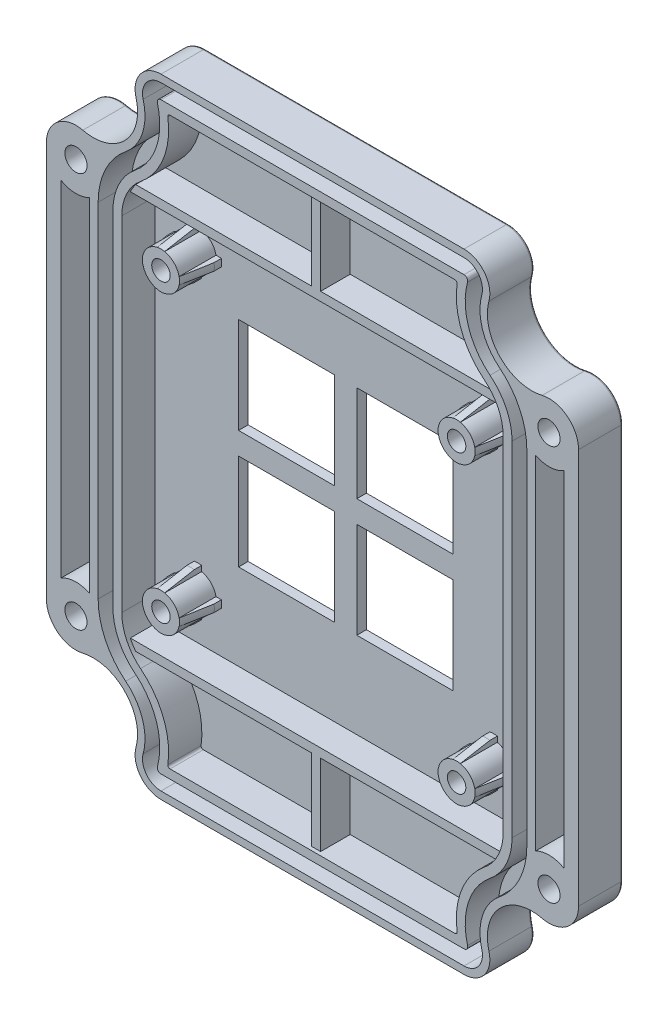
SolidWorks part; units mm, degrees
ref_plane "Front Plane" through (0, 0, 0) normal (0, 0, 1) x (1, 0, 0)
ref_plane "Top Plane" through (0, 0, 0) normal (0, 1, 0) x (1, 0, 0)
ref_plane "Right Plane" through (0, 0, 0) normal (1, 0, 0) x (0, 0, -1)
sketch "Sketch1" plane through (0, 0, 0) normal (0, 0, 1) x (1, 0, 0)
  line L12 (36, 85) -> (36, 0) construction
  line L13 (0, 42.5) -> (72, 42.5) construction
  line L14 (0, 69.25) -> (0, 15.75)
  line L15 (15.5, 0) -> (56.5, 0)
  line L16 (72, 15.75) -> (72, 69.25)
  line L17 (56.5, 85) -> (15.5, 85)
  arc A13 (12.1242, 80.5757) -> (4.9292, 73.1406) centre (6.3257, 78.9881) cw
  arc A14 (15.5, 85) -> (12.1242, 80.5757) centre (15.5, 81.5) ccw
  arc A15 (4.9292, 73.1406) -> (0, 69.25) centre (4, 69.25) ccw
  arc A16 (67.0708, 73.1406) -> (72, 69.25) centre (68, 69.25) cw
  arc A17 (56.5, 85) -> (59.8758, 80.5757) centre (56.5, 81.5) cw
  arc A18 (59.8758, 80.5757) -> (67.0708, 73.1406) centre (65.6743, 78.9881) ccw
  arc A19 (59.8758, 4.4243) -> (67.0708, 11.8594) centre (65.6743, 6.0119) cw
  arc A20 (56.5, 0) -> (59.8758, 4.4243) centre (56.5, 3.5) ccw
  arc A21 (67.0708, 11.8594) -> (72, 15.75) centre (68, 15.75) ccw
  arc A22 (4.9292, 11.8594) -> (0, 15.75) centre (4, 15.75) cw
  arc A23 (15.5, 0) -> (12.1242, 4.4243) centre (15.5, 3.5) cw
  arc A24 (12.1242, 4.4243) -> (4.9292, 11.8594) centre (6.3257, 6.0119) ccw
extrude "Boss-Extrude1" add sketch "Sketch1" along normal blind 6
sketch "Sketch2" plane through (0, 0, 6) normal (0, 0, 1) x (1, 0, 0)
  line L0 (36, 85) -> (36, 0) construction
  line L1 (0, 42.5) -> (72, 42.5) construction
  circle A0 centre (4, 69.25) radius 1.5
  circle A1 centre (68, 69.25) radius 1.5
  circle A2 centre (4, 15.75) radius 1.5
  circle A3 centre (68, 15.75) radius 1.5
  dimension "D1" = 3
extrude "Cut-Extrude1" cut sketch "Sketch2" against normal blind 6
sketch "Sketch3" plane through (0, 0, 0) normal (0, 0, -1) x (-1, 0, 0)
  circle A0 centre (-68, 69.25) radius 3
  circle A1 centre (-4, 69.25) radius 3
  circle A2 centre (-68, 15.75) radius 3
  circle A3 centre (-4, 15.75) radius 3
  dimension "D1" = 6
  dimension "D2" = 6
  dimension "D3" = 6
  dimension "D4" = 6
extrude "Cut-Extrude2" cut sketch "Sketch3" against normal blind 3
fillet "Fillet1" radius 0.3 20 edges at (0, 42.5, 0) (1.5218, 12.6102, 0) (10.646, 10.1927, 0) (12.7175, 1.3769, 0) (36, 0, 0) (59.2825, 1.3769, 0) (61.354, 10.1927, 0) (70.4782, 12.6102, 0) (72, 42.5, 0) (70.4782, 72.3898, 0) (61.354, 74.8073, 0) (59.2825, 83.6231, 0) (36, 85, 0) (12.7175, 83.6231, 0) (10.646, 74.8073, 0) (1.5218, 72.3898, 0) (65, 69.25, 0) (1, 15.75, 0) (65, 15.75, 0) (1, 69.25, 0)
sketch "Sketch4" plane through (0, 0, 0) normal (0, 0, -1) x (-1, 0, 0)
  line L1 (-58, 66.5) -> (-14, 66.5)
  line L2 (-60, 64.5) -> (-60, 20.5)
  line L3 (-58, 18.5) -> (-14, 18.5)
  line L4 (-12, 64.5) -> (-12, 20.5)
  line L5 (-36, 85) -> (-36, 0) construction
  line L6 (0, 42.5) -> (-72, 42.5) construction
  arc A0 (-60, 64.5) -> (-58, 66.5) centre (-58, 64.5) cw
  arc A1 (-12, 64.5) -> (-14, 66.5) centre (-14, 64.5) ccw
  arc A2 (-14, 18.5) -> (-12, 20.5) centre (-14, 20.5) ccw
  arc A3 (-58, 18.5) -> (-60, 20.5) centre (-58, 20.5) cw
  point P10 (-60, 66.5)
  point P15 (-12, 18.5)
  point P18 (-60, 18.5)
  dimension "D5" = 2
  dimension "D6" = 2
  dimension "D7" = 2
  dimension "D8" = 2
  dimension "D1" = 48
  dimension "D2" = 48
  dimension "D3" = 24
  dimension "D4" = 24
extrude "Cut-Extrude3" cut sketch "Sketch4" against normal blind 0.2
sketch "Sketch5" plane through (0, 0, 0.2) normal (0, 0, -1) x (-1, 0, 0)
  line L0 (-36, 85) -> (-36, 0) construction
  line L1 (-34.5, 57) -> (-21.5, 57)
  line L2 (-34.5, 57) -> (-34.5, 44)
  line L3 (-34.5, 44) -> (-21.5, 44)
  line L4 (-21.5, 57) -> (-21.5, 44)
  line L5 (0, 42.5) -> (-72, 42.5) construction
  line L6 (-36, 66.5) -> (-36, 18.5) construction
  line L7 (-14, 66.5) -> (-58, 66.5) construction
  line L8 (-58, 18.5) -> (-14, 18.5) construction
  line L9 (-60, 42.5) -> (-12, 42.5) construction
  line L10 (-60, 64.5) -> (-60, 20.5) construction
  line L11 (-12, 20.5) -> (-12, 64.5) construction
  line L12 (-50.5, 57) -> (-50.5, 44)
  line L13 (-37.5, 44) -> (-50.5, 44)
  line L14 (-37.5, 57) -> (-37.5, 44)
  line L15 (-37.5, 57) -> (-50.5, 57)
  line L16 (-37.5, 28) -> (-50.5, 28)
  line L17 (-37.5, 28) -> (-37.5, 41)
  line L18 (-37.5, 41) -> (-50.5, 41)
  line L19 (-50.5, 28) -> (-50.5, 41)
  line L20 (-21.5, 28) -> (-21.5, 41)
  line L21 (-34.5, 41) -> (-21.5, 41)
  line L22 (-34.5, 28) -> (-34.5, 41)
  line L23 (-34.5, 28) -> (-21.5, 28)
  point P6 (-28, 44)
  dimension "D1" = 13
  dimension "D2" = 13
  dimension "D3" = 1.5
  dimension "D4" = 1.5
extrude "Cut-Extrude4" cut sketch "Sketch5" against normal blind 5.8
sketch "Sketch6" plane through (0, 0, 6) normal (0, 0, 1) x (1, 0, 0)
  line L0 (7, 81.7875) -> (7, 6.0389) construction
  line L1 (0, 69.25) -> (0, 15.75) construction
  line L2 (65, 81.7875) -> (65, 3.4386) construction
  line L3 (72, 15.75) -> (72, 69.25) construction
  line L4 (2, 79.754) -> (2, -5.5734) construction
  line L5 (5.8, 81.7875) -> (5.8, -9.4813) construction
  line L6 (36, 85) -> (36, 0) construction
  line L7 (0, 42.5) -> (72, 42.5) construction
  line L8 (2, 65.7859) -> (2, 19.2141)
  line L9 (5.8, 65.6779) -> (5.8, 19.3221)
  line L10 (66.2, 65.6779) -> (66.2, 19.3221)
  line L11 (70, 65.7859) -> (70, 19.2141)
  line L12 (36, 85) -> (36, 0) construction
  line L13 (7, 19.2583) -> (7, 65.7417)
  line L14 (0, 42.5) -> (72, 42.5) construction
  line L15 (65, 19.2583) -> (65, 65.7417)
  line L16 (15.5, 84) -> (56.5, 84)
  line L25 (15.5, 1) -> (56.5, 1)
  arc A0 (2, 65.7859) -> (5.8, 65.6779) centre (4, 69.25) ccw
  arc A1 (4.9292, 73.1406) -> (0, 69.25) centre (4, 69.25) ccw construction
  arc A2 (2, 19.2141) -> (5.8, 19.3221) centre (4, 15.75) cw
  arc A3 (70, 19.2141) -> (66.2, 19.3221) centre (68, 15.75) ccw
  arc A4 (70, 65.7859) -> (66.2, 65.6779) centre (68, 69.25) cw
  arc A5 (15.5, 1) -> (13.0887, 4.1602) centre (15.5, 3.5) cw
  arc A6 (56.5, 1) -> (58.9113, 4.1602) centre (56.5, 3.5) ccw
  arc A8 (10.7254, 11.4718) -> (13.0887, 4.1602) centre (6.3257, 6.0119) cw
  arc A9 (61.2746, 11.4718) -> (58.9113, 4.1602) centre (65.6743, 6.0119) ccw
  arc A10 (7, 19.2583) -> (10.7254, 11.4718) centre (17, 19.2583) ccw
  arc A11 (65, 19.2583) -> (61.2746, 11.4718) centre (55, 19.2583) cw
  arc A12 (7, 65.7417) -> (10.7254, 73.5282) centre (17, 65.7417) cw
  arc A13 (10.7254, 73.5282) -> (13.0887, 80.8398) centre (6.3257, 78.9881) ccw
  arc A14 (15.5, 84) -> (13.0887, 80.8398) centre (15.5, 81.5) ccw
  arc A15 (56.5, 84) -> (58.9113, 80.8398) centre (56.5, 81.5) cw
  arc A16 (61.2746, 73.5282) -> (58.9113, 80.8398) centre (65.6743, 78.9881) cw
  arc A17 (65, 65.7417) -> (61.2746, 73.5282) centre (55, 65.7417) ccw
  point P42 (36, 1)
  point P54 (7.9793, 70.0576)
  point P60 (7.9793, 14.9424)
  point P62 (7, 42.5)
  point P76 (65, 42.5)
  dimension "D6" = 10
  dimension "D1" = 7
  dimension "D2" = 7
  dimension "D3" = 2
  dimension "D4" = 1.2
extrude "Cut-Extrude19" cut sketch "Sketch6" against normal blind 4.5
sketch "Sketch13" plane through (0, 0, 1.5) normal (0, 0, 1) x (1, 0, 0)
  line L2 (15.5, 82) -> (56.5, 82)
  line L3 (15.5, 3) -> (56.5, 3)
  line L5 (0, 42.5) -> (72, 42.5) construction
  line L6 (9, 65.7417) -> (9, 19.2583)
  line L7 (9, 65.7417) -> (9, 19.2583)
  line L8 (36, 85) -> (36, 0) construction
  line L9 (0, 42.5) -> (72, 42.5) construction
  line L10 (63, 65.7417) -> (63, 19.2583)
  arc A2 (11.9803, 71.9709) -> (15.0177, 81.368) centre (6.3257, 78.9881) ccw
  arc A3 (11.9803, 71.9709) -> (15.0177, 81.368) centre (6.3257, 78.9881) ccw
  arc A4 (15.0177, 81.368) -> (15.5, 82) centre (15.5, 81.5) cw
  arc A5 (11.9803, 71.9709) -> (9, 65.7417) centre (17, 65.7417) ccw
  arc A6 (11.9803, 71.9709) -> (9, 65.7417) centre (17, 65.7417) ccw
  arc A7 (60.0197, 71.9709) -> (63, 65.7417) centre (55, 65.7417) cw
  arc A8 (56.9823, 81.368) -> (56.5, 82) centre (56.5, 81.5) ccw
  arc A9 (60.0197, 71.9709) -> (56.9823, 81.368) centre (65.6743, 78.9881) cw
  arc A10 (56.9823, 3.632) -> (56.5, 3) centre (56.5, 3.5) cw
  arc A11 (15.0177, 3.632) -> (15.5, 3) centre (15.5, 3.5) ccw
  arc A12 (60.0197, 13.0291) -> (63, 19.2583) centre (55, 19.2583) ccw
  arc A13 (60.0197, 13.0291) -> (56.9823, 3.632) centre (65.6743, 6.0119) ccw
  arc A14 (11.9803, 13.0291) -> (15.0177, 3.632) centre (6.3257, 6.0119) cw
  arc A15 (11.9803, 13.0291) -> (9, 19.2583) centre (17, 19.2583) cw
  point P35 (63, 42.5)
  point P41 (9, 42.5)
  dimension "D5" = 0.5
  dimension "D2" = 2
  dimension "D3" = 2
  dimension "D4" = 2
extrude "Boss-Extrude4" add sketch "Sketch13" along normal blind 4.5
sketch "Sketch14" plane through (0, 0, 6) normal (0, 0, 1) x (1, 0, 0)
  line L0 (36, 85) -> (36, 0) construction
  line L1 (0, 42.5) -> (72, 42.5) construction
  line L4 (56.5, 80.8) -> (15.5, 80.8)
  line L5 (55.2716, 80.8) -> (16.7284, 80.8)
  line L6 (36, 85) -> (36, 0) construction
  line L7 (10.2, 65.7417) -> (10.2, 19.2583)
  line L8 (10.2, 65.7417) -> (10.2, 19.2583)
  line L9 (0, 42.5) -> (72, 42.5) construction
  line L10 (61.8, 65.7417) -> (61.8, 19.2583)
  line L11 (55.2716, 4.2) -> (16.7284, 4.2)
  arc A2 (12.7333, 71.0365) -> (16.1752, 81.6849) centre (6.3257, 78.9881) ccw
  arc A3 (12.7333, 71.0365) -> (16.4315, 80.4569) centre (6.3257, 78.9881) ccw
  arc A4 (16.4315, 80.4569) -> (16.7284, 80.8) centre (16.7284, 80.5) cw
  arc A5 (12.7333, 71.0365) -> (10.2, 65.7417) centre (17, 65.7417) ccw
  arc A6 (12.7333, 71.0365) -> (10.2, 65.7417) centre (17, 65.7417) ccw
  arc A7 (59.2667, 71.0365) -> (61.8, 65.7417) centre (55, 65.7417) cw
  arc A8 (59.2667, 71.0365) -> (55.5685, 80.4569) centre (65.6743, 78.9881) cw
  arc A9 (55.5685, 80.4569) -> (55.2716, 80.8) centre (55.2716, 80.5) ccw
  arc A10 (55.5685, 4.5431) -> (55.2716, 4.2) centre (55.2716, 4.5) cw
  arc A11 (16.4315, 4.5431) -> (16.7284, 4.2) centre (16.7284, 4.5) ccw
  arc A12 (59.2667, 13.9635) -> (61.8, 19.2583) centre (55, 19.2583) ccw
  arc A13 (59.2667, 13.9635) -> (55.5685, 4.5431) centre (65.6743, 6.0119) ccw
  arc A14 (12.7333, 13.9635) -> (16.4315, 4.5431) centre (6.3257, 6.0119) cw
  arc A15 (12.7333, 13.9635) -> (10.2, 19.2583) centre (17, 19.2583) cw
  point P35 (36, 80.8)
  point P42 (61.8, 42.5)
  point P48 (10.2, 42.5)
  dimension "D5" = 0.3
  dimension "D1" = 1.2
  dimension "D2" = 1.2
  dimension "D3" = 1.2
  dimension "D4" = 1.2
extrude "Cut-Extrude20" cut sketch "Sketch14" against normal blind 4.5
sketch "Sketch17" plane through (0, 0, 1.5) normal (0, 0, 1) x (1, 0, 0)
  line L0 (36, 85) -> (36, 0) construction
  line L1 (0, 42.5) -> (72, 42.5) construction
  line L2 (35.4, 85) -> (35.4, 0) construction
  line L3 (36.6, 85) -> (36.6, 0) construction
  line L4 (4, 69.25) -> (68, 69.25) construction
  line L5 (4, 68.65) -> (68, 68.65) construction
  line L6 (4, 69.85) -> (68, 69.85) construction
  line L7 (10.8533, 68.65) -> (61.1467, 68.65)
  line L8 (60.4187, 69.85) -> (36.6, 69.85)
  line L9 (36.6, 69.85) -> (36.6, 80.8)
  line L10 (55.2716, 80.8) -> (16.7284, 80.8) construction
  line L11 (36.6, 80.8) -> (35.4, 80.8)
  line L12 (35.4, 80.8) -> (35.4, 69.85)
  line L13 (35.4, 69.85) -> (11.5813, 69.85)
  line L14 (60.4187, 15.15) -> (36.6, 15.15)
  line L15 (10.8533, 16.35) -> (61.1467, 16.35)
  line L16 (35.4, 15.15) -> (11.5813, 15.15)
  line L17 (35.4, 4.2) -> (35.4, 15.15)
  line L18 (36.6, 4.2) -> (35.4, 4.2)
  line L19 (36.6, 15.15) -> (36.6, 4.2)
  arc A1 (12.7333, 71.0365) -> (10.2, 65.7417) centre (17, 65.7417) ccw construction
  arc A2 (12.7333, 71.0365) -> (10.2, 65.7417) centre (17, 65.7417) ccw
  arc A3 (11.5813, 69.85) -> (10.8533, 68.65) centre (17, 65.7417) ccw
  arc A4 (12.7333, 71.0365) -> (10.2, 65.7417) centre (17, 65.7417) ccw construction
  arc A7 (61.8, 65.7417) -> (59.2667, 71.0365) centre (55, 65.7417) ccw
  arc A8 (61.1467, 68.65) -> (60.4187, 69.85) centre (55, 65.7417) ccw
  arc A9 (61.8, 65.7417) -> (59.2667, 71.0365) centre (55, 65.7417) ccw construction
  arc A10 (61.8, 65.7417) -> (59.2667, 71.0365) centre (55, 65.7417) ccw construction
  arc A11 (61.1467, 16.35) -> (60.4187, 15.15) centre (55, 19.2583) cw
  arc A12 (11.5813, 15.15) -> (10.8533, 16.35) centre (17, 19.2583) cw
  dimension "D1" = 0.6
  dimension "D3" = 0.6
  dimension "D6" = 0
  dimension "D2" = 0.6
  dimension "D4" = 0.6
  dimension "D5" = 0
extrude "Boss-Extrude5" add sketch "Sketch17" along normal blind 4
sketch "Sketch21" plane through (0, 0, 1.5) normal (0, 0, 1) x (1, 0, 0)
  line L0 (36, 85) -> (36, 0) construction
  line L1 (0, 42.5) -> (72, 42.5) construction
  line L2 (-7.6968, 62.5) -> (78.227, 62.5) construction
  line L3 (16, 93.8643) -> (16, -8.0503) construction
  line L4 (0, 69.25) -> (0, 15.75) construction
  line L5 (56.5, 85) -> (15.5, 85) construction
  circle A1 centre (16, 62.5) radius 2.5
  circle A2 centre (56, 62.5) radius 2.5
  circle A3 centre (56, 22.5) radius 2.5
  circle A4 centre (16, 22.5) radius 2.5
  dimension "D4" = 5
  dimension "D1" = 16
  dimension "D2" = 22.5
extrude "Boss-Extrude6" add sketch "Sketch21" along normal blind 5
sketch "Sketch22" plane through (0, 0, 6.5) normal (0, 0, 1) x (1, 0, 0)
  line L0 (36, 85) -> (36, 0) construction
  line L1 (0, 42.5) -> (72, 42.5) construction
  circle A1 centre (16, 62.5) radius 1.25
  circle A2 centre (16, 62.5) radius 2.5 construction
  circle A3 centre (56, 62.5) radius 1.25
  circle A4 centre (56, 22.5) radius 1.25
  circle A5 centre (16, 22.5) radius 1.25
  dimension "D1" = 2.5
extrude "Cut-Extrude21" cut sketch "Sketch22" against normal blind 5
sketch "Sketch23" plane through (0, 0, 1.5) normal (0, 0, 1) x (1, 0, 0)
  line L0 (18.5, 62.5) -> (13.5, 62.5) construction
  line L1 (18.5, 63) -> (13.5, 63) construction
  line L2 (18.5, 62) -> (13.5, 62) construction
  line L3 (18.4495, 63) -> (19.1802, 63)
  line L4 (18.4495, 62) -> (19.1802, 62)
  line L5 (36, 0) -> (36, 85) construction
  line L6 (0, 42.5) -> (72, 42.5) construction
  line L7 (53.5505, 63) -> (52.8198, 63)
  line L8 (53.5505, 62) -> (52.8198, 62)
  line L9 (53.5505, 22) -> (52.8198, 22)
  line L10 (53.5505, 23) -> (52.8198, 23)
  line L11 (18.4495, 22) -> (19.1802, 22)
  line L12 (18.4495, 23) -> (19.1802, 23)
  line L13 (16, 65) -> (16, 60) construction
  line L14 (15.5, 65) -> (15.5, 59.4411) construction
  line L15 (16.5, 65) -> (16.5, 59.4411) construction
  line L16 (16.5, 65) -> (16.5, 60) construction
  line L17 (15.5, 65) -> (15.5, 60) construction
  line L18 (15.5, 60.0505) -> (15.5, 59.3198)
  line L19 (16.5, 60.0505) -> (16.5, 59.3198)
  line L20 (15.5, 24.9495) -> (15.5, 25.6802)
  line L21 (16.5, 24.9495) -> (16.5, 25.6802)
  line L22 (56.5, 60.0505) -> (56.5, 59.3198)
  line L23 (55.5, 60.0505) -> (55.5, 59.3198)
  line L24 (55.5, 24.9495) -> (55.5, 25.6802)
  line L25 (56.5, 24.9495) -> (56.5, 25.6802)
  line L26 (56, 62.5) -> (56, 65) construction
  line L27 (56, 62.5) -> (58.5, 62.5) construction
  line L28 (58.4495, 63) -> (59.1802, 63)
  line L29 (58.4495, 62) -> (59.1802, 62)
  line L30 (55.5, 64.9495) -> (55.5, 65.6802)
  line L31 (56.5, 64.9495) -> (56.5, 65.6802)
  line L32 (15.5, 64.9495) -> (15.5, 65.6802)
  line L33 (16.5, 64.9495) -> (16.5, 65.6802)
  line L34 (13.5505, 62) -> (12.8198, 62)
  line L35 (13.5505, 63) -> (12.8198, 63)
  line L36 (13.5505, 22) -> (12.8198, 22)
  line L37 (13.5505, 23) -> (12.8198, 23)
  line L38 (16.5, 20.0505) -> (16.5, 19.3198)
  line L39 (15.5, 20.0505) -> (15.5, 19.3198)
  line L40 (56.5, 20.0505) -> (56.5, 19.3198)
  line L41 (55.5, 20.0505) -> (55.5, 19.3198)
  line L42 (58.4495, 23) -> (59.1802, 23)
  line L43 (58.4495, 22) -> (59.1802, 22)
  arc A0 (18.4495, 63) -> (18.4495, 62) centre (16, 62.5) cw
  circle A1 centre (16, 62.5) radius 2.5 construction
  circle A2 centre (16, 62.5) radius 2.5 construction
  arc A3 (19.1802, 63) -> (19.1802, 62) centre (16, 62.5) cw
  arc A4 (53.5505, 63) -> (53.5505, 62) centre (56, 62.5) ccw
  arc A5 (52.8198, 63) -> (52.8198, 62) centre (56, 62.5) ccw
  arc A6 (52.8198, 22) -> (52.8198, 23) centre (56, 22.5) cw
  arc A7 (53.5505, 22) -> (53.5505, 23) centre (56, 22.5) cw
  arc A8 (18.4495, 22) -> (18.4495, 23) centre (16, 22.5) ccw
  arc A9 (19.1802, 22) -> (19.1802, 23) centre (16, 22.5) ccw
  arc A10 (16.5, 24.9495) -> (15.5, 24.9495) centre (16, 22.5) ccw
  arc A11 (16.5, 25.6802) -> (15.5, 25.6802) centre (16, 22.5) ccw
  arc A12 (16.5, 59.3198) -> (15.5, 59.3198) centre (16, 62.5) cw
  arc A13 (16.5, 60.0505) -> (15.5, 60.0505) centre (16, 62.5) cw
  arc A14 (55.5, 60.0505) -> (56.5, 60.0505) centre (56, 62.5) ccw
  arc A15 (55.5, 59.3198) -> (56.5, 59.3198) centre (56, 62.5) ccw
  arc A16 (55.5, 25.6802) -> (56.5, 25.6802) centre (56, 22.5) cw
  arc A17 (55.5, 24.9495) -> (56.5, 24.9495) centre (56, 22.5) cw
  circle A18 centre (56, 62.5) radius 2.5 construction
  arc A19 (59.1802, 63) -> (59.1802, 62) centre (56, 62.5) cw
  arc A20 (58.4495, 63) -> (58.4495, 62) centre (56, 62.5) cw
  arc A21 (55.5, 65.6802) -> (56.5, 65.6802) centre (56, 62.5) cw
  arc A22 (55.5, 64.9495) -> (56.5, 64.9495) centre (56, 62.5) cw
  arc A23 (16.5, 64.9495) -> (15.5, 64.9495) centre (16, 62.5) ccw
  arc A24 (16.5, 65.6802) -> (15.5, 65.6802) centre (16, 62.5) ccw
  arc A25 (13.5505, 63) -> (13.5505, 62) centre (16, 62.5) ccw
  arc A26 (12.8198, 63) -> (12.8198, 62) centre (16, 62.5) ccw
  arc A27 (12.8198, 22) -> (12.8198, 23) centre (16, 22.5) cw
  arc A28 (13.5505, 22) -> (13.5505, 23) centre (16, 22.5) cw
  arc A29 (16.5, 19.3198) -> (15.5, 19.3198) centre (16, 22.5) cw
  arc A30 (16.5, 20.0505) -> (15.5, 20.0505) centre (16, 22.5) cw
  arc A31 (55.5, 20.0505) -> (56.5, 20.0505) centre (56, 22.5) ccw
  arc A32 (55.5, 19.3198) -> (56.5, 19.3198) centre (56, 22.5) ccw
  arc A33 (58.4495, 22) -> (58.4495, 23) centre (56, 22.5) ccw
  arc A34 (59.1802, 22) -> (59.1802, 23) centre (56, 22.5) ccw
  dimension "D1" = 0.5
  dimension "D3" = 0.5
  dimension "D2" = 0.5
  dimension "D4" = 0.5
extrude "Boss-Extrude9" add sketch "Sketch23" along normal blind 5
chamfer "Chamfer2" distance 4 angle 10 1 edges at (16, 59.2808, 6.5)
chamfer "Chamfer3" distance 4 angle 10 3 edges at (12.7808, 62.5, 6.5) (16, 65.7192, 6.5) (19.2192, 62.5, 6.5)
chamfer "Chamfer4" distance 4 angle 10 12 edges at (16, 19.2808, 6.5) (12.7808, 22.5, 6.5) (16, 25.7192, 6.5) (19.2192, 22.5, 6.5) (56, 25.7192, 6.5) (52.7808, 22.5, 6.5) (56, 19.2808, 6.5) (59.2192, 22.5, 6.5) (56, 65.7192, 6.5) (52.7808, 62.5, 6.5) (56, 59.2808, 6.5) (59.2192, 62.5, 6.5)
